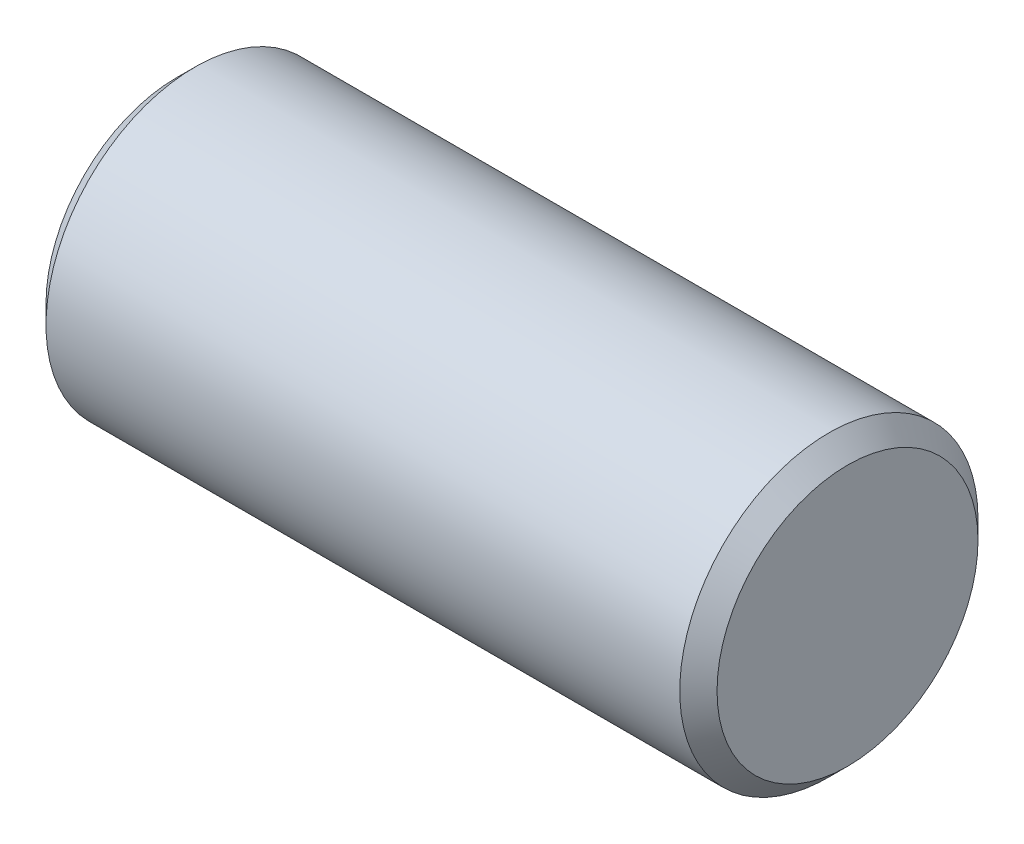
SolidWorks part; units mm, degrees
ref_plane "Piano frontale" through (0, 0, 0) normal (0, 0, 1) x (1, 0, 0)
ref_plane "Piano superiore" through (0, 0, 0) normal (0, 1, 0) x (1, 0, 0)
ref_plane "Piano destro" through (0, 0, 0) normal (1, 0, 0) x (0, 0, -1)
sketch "Schizzo1" [suppressed] plane through (0, 0, 0) normal (1, 0, 0) x (0, 0, -1)
  circle A0 centre (0, 0) radius 3
  dimension "D1" = 6
extrude "Estrusione-Estrusione1" [suppressed] add sketch "Schizzo1" along normal blind 30
chamfer "Smusso1" [suppressed] distance 0.5 angle 45
sketch "Schizzo2" plane through (0, 0, 0) normal (1, 0, 0) x (0, 0, -1)
  circle A0 centre (0, 0) radius 4
  dimension "D1" = 8
extrude "Estrusione-Estrusione2" add sketch "Schizzo2" along normal blind 18
chamfer "Smusso2" distance 0.5 angle 45 2 edges at (18, 0, -4) (0, 0, -4)
